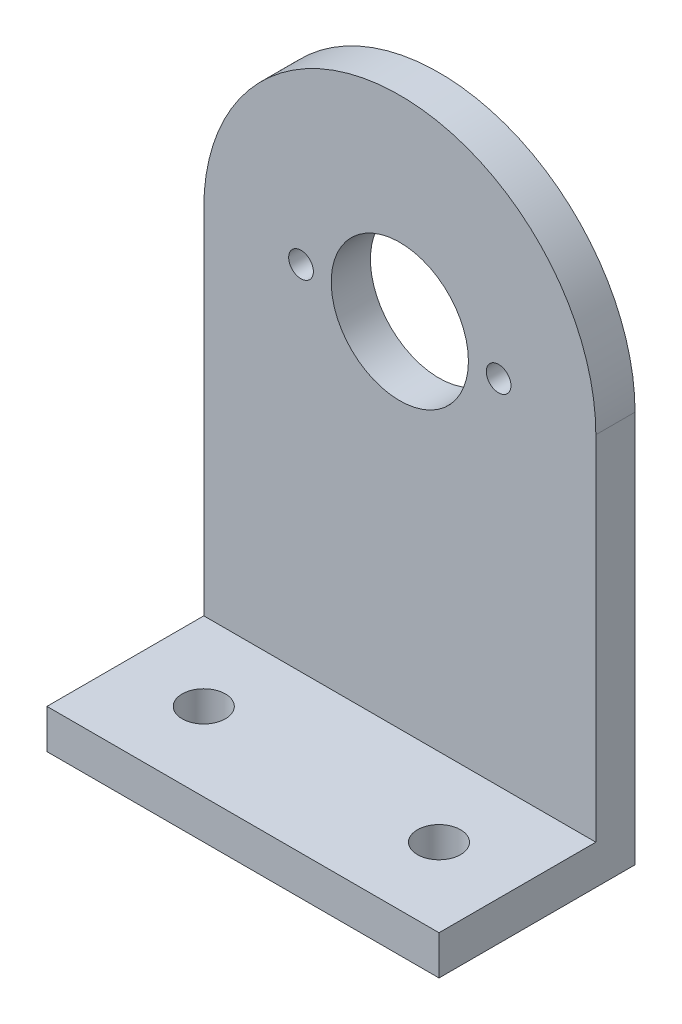
SolidWorks part; units mm, degrees
ref_plane "Front Plane" through (0, 0, 0) normal (0, 0, 1) x (1, 0, 0)
ref_plane "Top Plane" through (0, 0, 0) normal (0, 1, 0) x (1, 0, 0)
ref_plane "Right Plane" through (0, 0, 0) normal (1, 0, 0) x (0, 0, -1)
sketch "Sketch1" plane through (0, 0, 0) normal (0, 0, 1) x (1, 0, 0)
  line L1 (-15.875, 0) -> (15.875, 0)
  line L2 (-15.875, 0) -> (-15.875, -31.75)
  line L3 (-15.875, -31.75) -> (15.875, -31.75)
  line L4 (15.875, 0) -> (15.875, -31.75)
  circle A0 centre (0, 0) radius 15.875
  arc A2 (-15.875, 0) -> (15.875, 0) centre (0, 0) ccw
  dimension "D1" = 31.75
  dimension "D2" = 31.75
extrude "Boss-Extrude1" add sketch "Sketch1" along normal blind 3.175
sketch "Sketch3" plane through (0, 0, 3.175) normal (0, 0, 1) x (1, 0, 0)
  circle A0 centre (0, 0) radius 5.5562
  dimension "D1" = 11.1125
extrude "Cut-Extrude1" cut sketch "Sketch3" against normal through all
sketch "Sketch4" plane through (0, 0, 3.175) normal (0, 0, 1) x (1, 0, 0)
  line L0 (15.875, 0) -> (15.875, -31.75) construction
  line L1 (-15.875, -31.75) -> (15.875, -31.75)
  line L2 (-15.875, -31.75) -> (-15.875, -28.575)
  line L3 (-15.875, -28.575) -> (15.875, -28.575)
  line L4 (15.875, -31.75) -> (15.875, -28.575)
  dimension "D1" = 3.175
extrude "Boss-Extrude2" add sketch "Sketch4" along normal blind 12.7
sketch "Sketch5" plane through (0, -28.575, 0) normal (0, 1, 0) x (1, 0, 0)
  line L0 (-15.875, -9.525) -> (15.875, -9.525) construction
  line L1 (-15.875, -15.875) -> (-15.875, -3.175) construction
  line L2 (15.875, -15.875) -> (15.875, -3.175) construction
  line L3 (0, -3.175) -> (0, -15.875) construction
  line L4 (15.875, -3.175) -> (-15.875, -3.175) construction
  line L5 (15.875, -15.875) -> (-15.875, -15.875) construction
  circle A0 centre (-9.525, -9.525) radius 1.75
  circle A1 centre (9.525, -9.525) radius 1.75
  dimension "D1" = 3.5
  dimension "D2" = 9.525
extrude "Cut-Extrude2" cut sketch "Sketch5" against normal through all
hole_wizard "Ø2.0mm Dowel Hole1" positions "Sketch8" profile "Sketch9" hole size "Ø2.0" standard "ANSI Metric"
sketch "Sketch8" plane through (0, 0, 3.175) normal (0, 0, 1) x (1, 0, 0)
  line L0 (-15.875, 0) -> (15.875, 0) construction
  point P0 (-8.001, 0)
  point P2 (8.001, 0)
  dimension "D1" = 16.002
  dimension "D2" = 8.001
sketch "Sketch9" plane through (-8.001, 0, 3.175) normal (1, 0, 0) x (0, -1, 0)
  line L0 (0, 0) -> (0, 13.3009)
  line L1 (0, 13.3009) -> (1, 12.7)
  line L2 (1, 12.7) -> (1, 0)
  line L5 (1, 0) -> (0, 0)
  line L10 (0, 13.3009) -> (-1, 12.7) construction
  line L11 (0, -6.35) -> (0, 107.95) construction
  dimension "Hole Dia." = 2
  dimension "Hole Depth" = 12.7
  dimension "Drill Angle" = 118
chamfer "Chamfer1" distance 0.762 angle 45 2 edges at (-7.001, 0, 0) (9.001, 0, 0)
